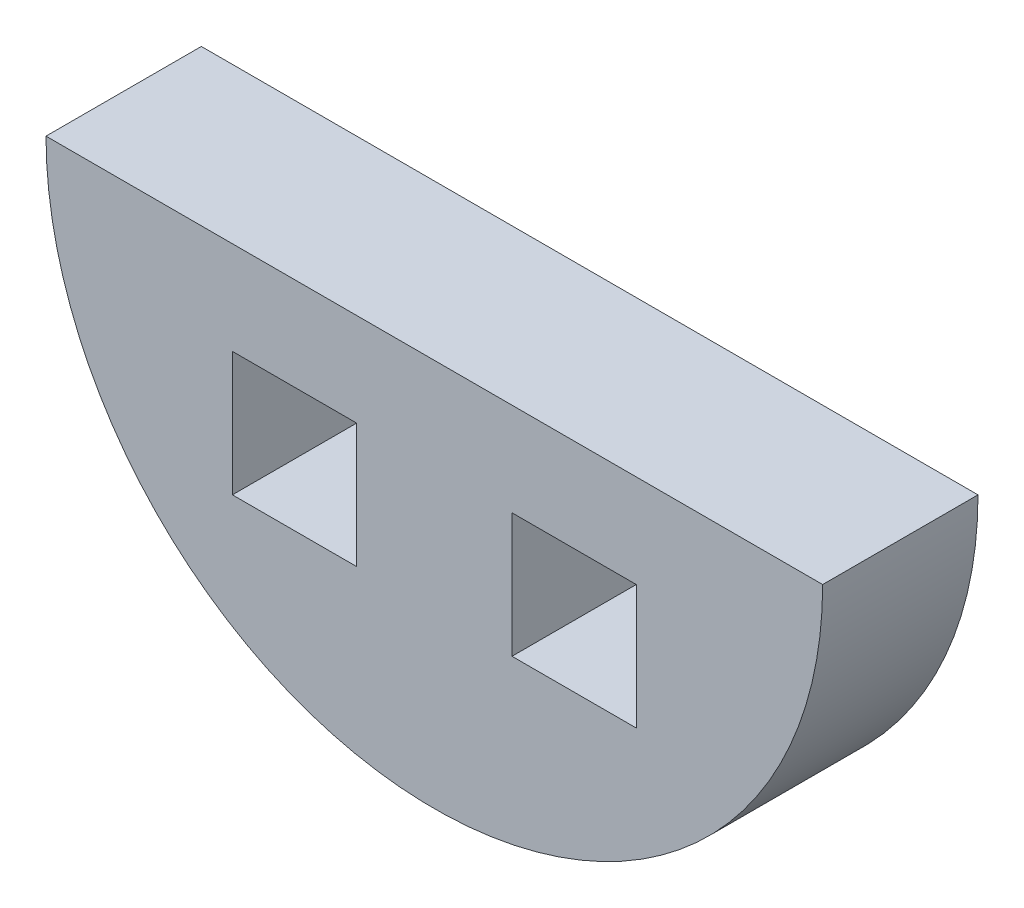
SolidWorks part; units mm, degrees
ref_plane "Front Plane" through (0, 0, 0) normal (0, 0, 1) x (1, 0, 0)
ref_plane "Top Plane" through (0, 0, 0) normal (0, 1, 0) x (1, 0, 0)
ref_plane "Right Plane" through (0, 0, 0) normal (1, 0, 0) x (0, 0, -1)
sketch "Sketch1" plane through (0, 0, 0) normal (0, 0, 1) x (1, 0, 0)
  line L0 (-125, 0) -> (0, 0)
  line L3 (-50, -35) -> (-30, -35)
  line L4 (-50, -35) -> (-50, -15)
  line L5 (-50, -15) -> (-30, -15)
  line L6 (-30, -35) -> (-30, -15)
  line L7 (-95, -35) -> (-75, -35)
  line L8 (-95, -35) -> (-95, -15)
  line L9 (-95, -15) -> (-75, -15)
  line L10 (-75, -35) -> (-75, -15)
  arc A1 (-125, 0) -> (0, 0) centre (-62.5, 0) ccw
  dimension "D1" = 30
  dimension "D7" = 62.5
  dimension "D2" = 15
  dimension "D3" = 30
  dimension "D4" = 20
extrude "Boss-Extrude1" add sketch "Sketch1" along normal blind 25
